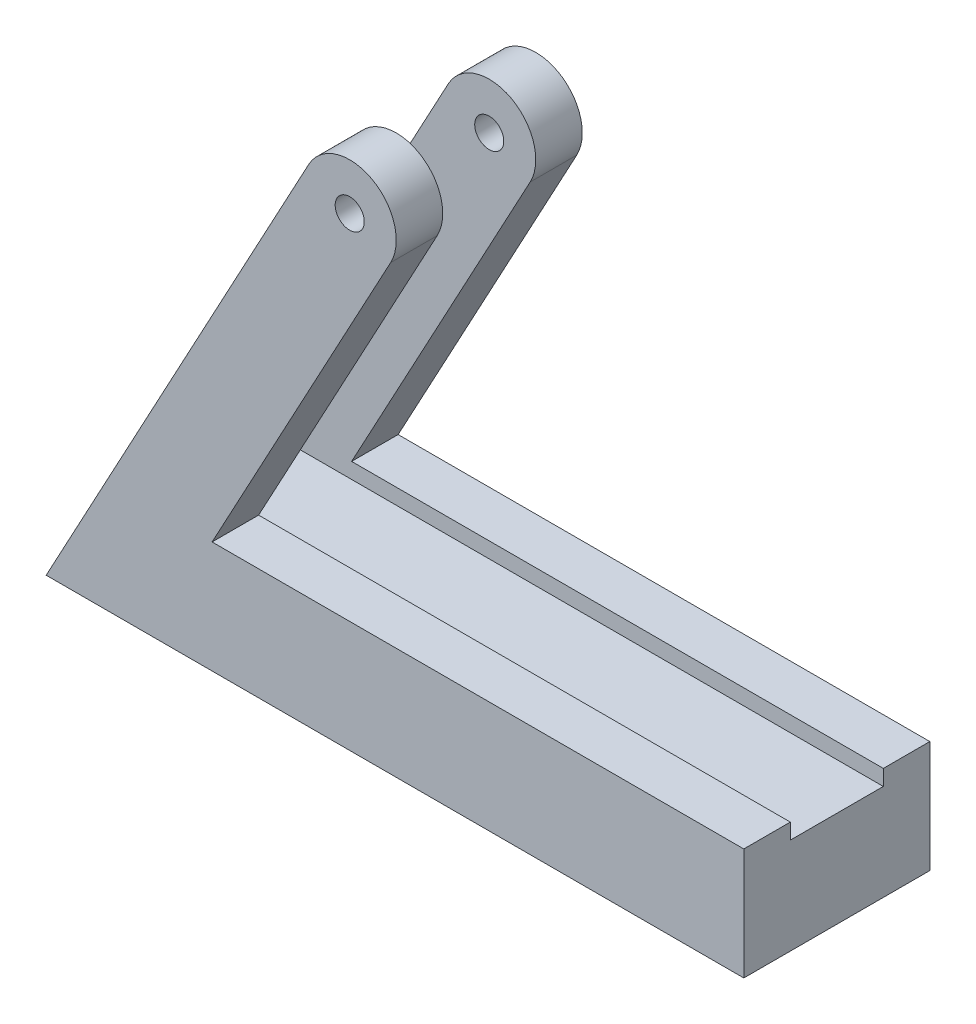
SolidWorks part; units mm, degrees
ref_plane "前基準面" through (0, 0, 0) normal (0, 0, 1) x (1, 0, 0)
ref_plane "上基準面" through (0, 0, 0) normal (0, 1, 0) x (1, 0, 0)
ref_plane "右基準面" through (0, 0, 0) normal (1, 0, 0) x (0, 0, -1)
sketch "草圖1" plane through (0, 0, 0) normal (0, 0, 1) x (1, 0, 0)
  line L0 (0, 0) -> (11.2927, 20.949)
  line L1 (14.8137, 19.051) -> (7.1351, 4.8064)
  line L2 (7.1351, 4.8064) -> (30, 4.8064)
  line L3 (30, 4.8064) -> (30, 0)
  line L4 (30, 0) -> (0, 0)
  arc A0 (11.2927, 20.949) -> (14.8137, 19.051) centre (13.0532, 20) cw
  point P7 (14.5377, 20)
  point P9 (30, 0)
  point P10 (10.3549, 21.3111)
  dimension "D3" = 30
  dimension "D1" = 2
  dimension "D2" = 20
extrude "填料-伸長1" add sketch "草圖1" against normal blind 8
sketch "草圖2" plane through (30, 0, 0) normal (1, 0, 0) x (0, 0, -1)
  line L1 (2, 4.1337) -> (6, 4.1337)
  line L2 (2, 4.1337) -> (2, 23)
  line L3 (2, 23) -> (6, 23)
  line L4 (6, 4.1337) -> (6, 23)
  line L6 (0, 4.8064) -> (0, 19.051) construction
  line L7 (8, 4.8064) -> (8, 19.051) construction
  dimension "D1" = 2
  dimension "D2" = 2
extrude "除料-伸長1" cut sketch "草圖2" against normal blind 88
sketch "草圖3" plane through (0, 0, 0) normal (0, 0, 1) x (1, 0, 0)
  circle A0 centre (13.0532, 20) radius 0.625
  dimension "D1" = 1.25
extrude "除料-伸長2" cut sketch "草圖3" against normal blind 88
